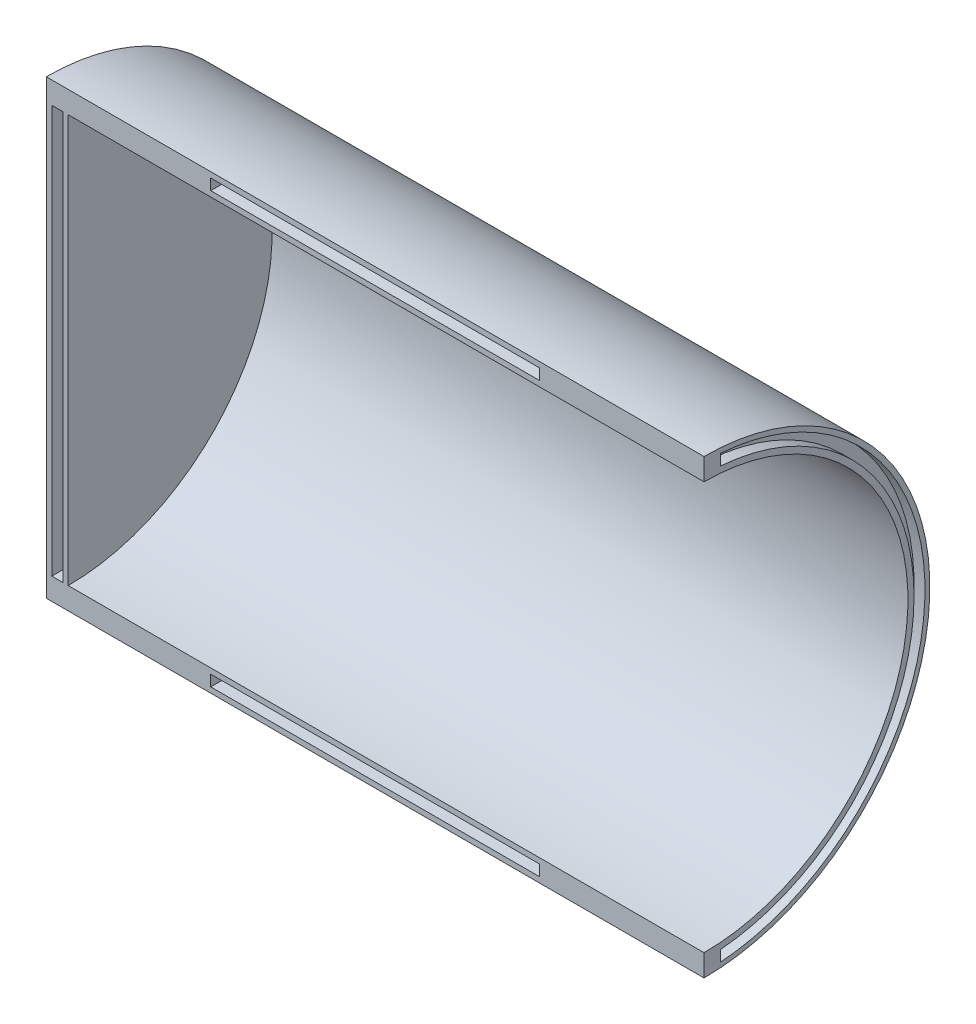
SolidWorks part; units mm, degrees
ref_plane "Front Plane" through (0, 0, 0) normal (0, 0, 1) x (1, 0, 0)
ref_plane "Top Plane" through (0, 0, 0) normal (0, 1, 0) x (1, 0, 0)
ref_plane "Right Plane" through (0, 0, 0) normal (1, 0, 0) x (0, 0, -1)
sketch "Sketch1" plane through (0, 0, 0) normal (0, 0, 1) x (1, 0, 0)
  line L0 (0, 0) -> (0, 52.324)
  line L1 (0, 52.324) -> (152.4, 52.324)
  line L2 (152.4, 52.324) -> (152.4, 47.244)
  line L3 (152.4, 47.244) -> (5.08, 47.244)
  line L4 (5.08, 47.244) -> (5.08, 0)
  line L5 (5.08, 0) -> (0, 0)
  dimension "D1" = 52.324
  dimension "D2" = 152.4
  dimension "D3" = 5.08
  dimension "D4" = 5.08
revolve "Revolve1" add sketch "Sketch1" angle 180 about L5
sketch "Sketch4" plane through (0, 0, 0) normal (0, 0, 1) x (1, 0, 0)
  line L0 (5.08, -47.244) -> (0, -47.244) construction
  line L1 (3.81, -47.244) -> (1.27, -47.244)
  line L2 (3.81, -47.244) -> (3.81, 47.244)
  line L3 (3.81, 47.244) -> (1.27, 47.244)
  line L4 (1.27, -47.244) -> (1.27, 47.244)
  line L5 (0, -52.324) -> (0, 52.324) construction
  line L9 (152.4, 52.324) -> (0, 52.324) construction
  line L10 (38.1, 48.514) -> (114.3, 48.514)
  line L11 (38.1, 48.514) -> (38.1, 51.054)
  line L12 (38.1, 51.054) -> (114.3, 51.054)
  line L13 (114.3, 48.514) -> (114.3, 51.054)
  line L14 (152.4, 52.324) -> (152.4, 47.244) construction
  line L15 (0, 0) -> (152.4, 0) construction
  line L16 (152.4, -47.244) -> (152.4, 47.244) construction
  line L17 (38.1, -51.054) -> (114.3, -51.054)
  line L18 (114.3, -48.514) -> (114.3, -51.054)
  line L19 (38.1, -48.514) -> (114.3, -48.514)
  line L20 (38.1, -48.514) -> (38.1, -51.054)
  point P9 (2.54, -47.244)
  point P10 (2.54, -47.244)
  point P17 (76.2, 52.324)
  point P18 (76.2, 51.054)
  point P23 (152.4, 49.784)
  point P24 (114.3, 49.784)
  dimension "D1" = 2.54
  dimension "D2" = 94.488
  dimension "D3" = 2.54
  dimension "D4" = 76.2
extrude "Cut-Extrude1" cut sketch "Sketch4" against normal blind 2.54 contours L11 L10 L13 L12 | L2 L1 L4 L3 | L17 L18 L19 L20
sketch "Sketch5" plane through (152.4, 0, 0) normal (1, 0, 0) x (0, 0, -1)
  line L0 (3.81, 51.054) -> (3.81, 48.514)
  line L1 (0, 0) -> (52.324, 0) construction
  line L2 (3.81, -51.054) -> (3.81, -48.514)
  line L3 (0, 52.324) -> (0, 47.244) construction
  line L4 (0, 47.244) -> (0, 52.324) construction
  line L5 (3.81, 48.514) -> (0, 48.514) construction
  arc A0 (3.81, -51.054) -> (3.81, 51.054) centre (0, 0) ccw
  arc A1 (3.81, -48.514) -> (3.81, 48.514) centre (0, 0) ccw
  arc A2 (0, -52.324) -> (0, 52.324) centre (0, 0) ccw construction
  point P15 (3.81, 49.784)
  point P17 (0, 49.784)
  dimension "D1" = 2.54
  dimension "D2" = 3.81
extrude "Cut-Extrude2" cut sketch "Sketch5" against normal blind 2.54
